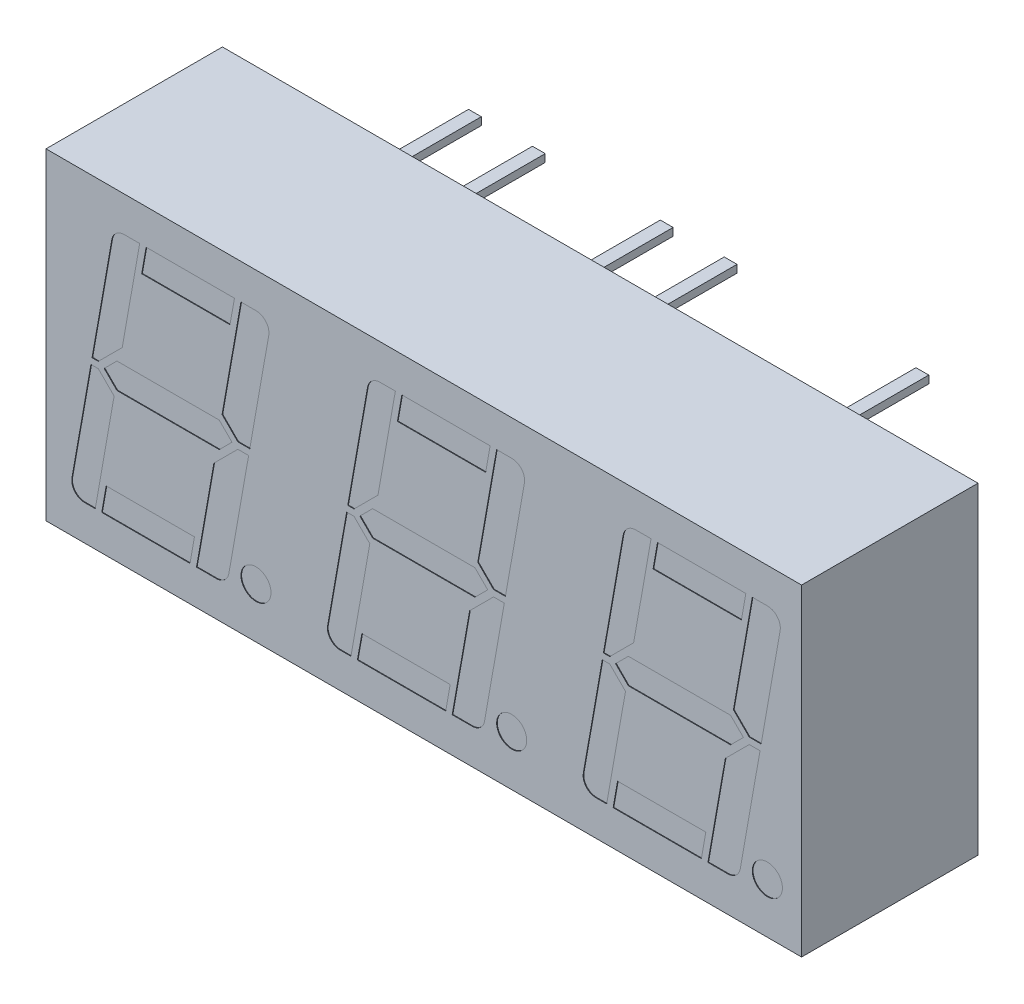
SolidWorks part; units mm, degrees
ref_plane "Front Plane" through (0, 0, 0) normal (0, 0, 1) x (1, 0, 0)
ref_plane "Top Plane" through (0, 0, 0) normal (0, 1, 0) x (1, 0, 0)
ref_plane "Right Plane" through (0, 0, 0) normal (1, 0, 0) x (0, 0, -1)
sketch "Sketch1" plane through (0, 0, 0) normal (0, 0, 1) x (1, 0, 0)
  line L0 (-15.0114, -6.4008) -> (15.0114, 6.4008) construction
  line L1 (-15.0114, 6.4008) -> (15.0114, 6.4008)
  line L2 (-15.0114, 6.4008) -> (-15.0114, -6.4008)
  line L3 (-15.0114, -6.4008) -> (15.0114, -6.4008)
  line L4 (15.0114, 6.4008) -> (15.0114, -6.4008)
  point P4 (0, 0)
  dimension "D1" = 12.8016
  dimension "D2" = 30.0228
extrude "Boss-Extrude1" add sketch "Sketch1" along normal blind 7.0104
sketch "Sketch2" plane through (0, 0, 0) normal (0, 0, -1) x (-1, 0, 0)
  line L0 (-15.0114, 0) -> (15.0114, 0) construction
  line L1 (-15.0114, -6.4008) -> (-15.0114, 6.4008) construction
  line L2 (15.0114, 6.4008) -> (15.0114, -6.4008) construction
  line L3 (0, 6.4008) -> (0, -6.4008) construction
  line L4 (-15.0114, 6.4008) -> (15.0114, 6.4008) construction
  line L5 (15.0114, -6.4008) -> (-15.0114, -6.4008) construction
  line L6 (-1.27, 5.2324) -> (-1.27, 4.9276) construction
  line L7 (-1.524, 5.2324) -> (-1.016, 5.2324)
  line L8 (-1.524, 5.2324) -> (-1.524, 4.9276)
  line L9 (-1.524, 4.9276) -> (-1.016, 4.9276)
  line L10 (-1.016, 5.2324) -> (-1.016, 4.9276)
  line L12 (-1.524, 5.08) -> (-1.016, 5.08) construction
  dimension "D1" = 0.508
  dimension "D2" = 0.3048
  dimension "D3" = 1.27
  dimension "D4" = 5.08
extrude "Boss-Extrude2" add sketch "Sketch2" along normal blind 3.9116
pattern_linear "LPattern1" count 4 spacing 2.54 along (1, 0, 0) count 2 spacing 10.16 along (0, -1, 0) skipping (1, 0), (2, 0) of "Boss-Extrude2"
pattern_linear "LPattern2" count 5 spacing 2.54 along (-1, 0, 0) count 2 spacing 10.16 along (0, -1, 0) skipping (0, 1), (2, 0), (4, 1) of "Boss-Extrude2"
sketch "Sketch3" plane through (0, 0, 7.0104) normal (0, 0, 1) x (1, 0, 0)
  line L0 (15.0114, 6.4008) -> (-15.0114, 6.4008) construction
  line L1 (-15.0114, -6.4008) -> (15.0114, -6.4008) construction
  line L3 (-15.0114, 0) -> (15.0114, 0) construction
  line L6 (0.8823, 5.0038) -> (-0.8823, -5.0038) construction
  line L7 (-2.54, 0) -> (-2.032, 0.508)
  line L8 (-2.032, 0.508) -> (2.032, 0.508)
  line L9 (-2.7722, 0.127) -> (-1.8218, 1.0774)
  line L10 (-1.8218, 1.0774) -> (-1.1295, 5.0038)
  line L11 (-1.1295, 5.0038) -> (-1.7349, 5.0038)
  line L12 (-2.2352, 4.584) -> (-3.021, 0.127)
  line L13 (-3.021, 0.127) -> (-2.7722, 0.127)
  line L14 (0.8823, 5.0038) -> (-0.8715, 5.0038)
  line L15 (-0.8715, 5.0038) -> (-1.048, 4.0032)
  line L16 (-1.048, 4.0032) -> (0.7059, 4.0032)
  line L17 (0, -6.4008) -> (0, 6.4008) construction
  line L18 (-2.032, -0.508) -> (2.032, -0.508)
  line L19 (-2.54, 0) -> (-2.032, -0.508)
  line L20 (2.54, 0) -> (2.032, 0.508)
  line L21 (-2.286, 0.254) -> (-2.4656, 0.4336) construction
  line L22 (-0.9598, 4.5035) -> (-1.2099, 4.5476) construction
  line L23 (-1.9148, 6.4008) -> (-3.0434, 0) construction
  line L24 (2.54, 0) -> (2.032, -0.508)
  line L25 (3.245, 0.127) -> (2.7722, 0.127)
  line L26 (2.7722, 0.127) -> (2.1448, 0.7544)
  line L27 (2.1448, 0.7544) -> (2.8941, 5.0038)
  line L28 (2.8941, 5.0038) -> (3.4995, 5.0038)
  line L29 (3.9998, 4.4076) -> (3.245, 0.127)
  line L30 (1.914, -5.0038) -> (1.1295, -5.0038)
  line L31 (-2.286, -0.254) -> (-2.4656, -0.4336) construction
  line L32 (1.1295, -5.0038) -> (1.8218, -1.0774)
  line L33 (-3.0658, -0.127) -> (-2.7722, -0.127)
  line L34 (3.2002, -0.127) -> (2.4143, -4.584)
  line L35 (-2.8941, -5.0038) -> (-3.3203, -5.0038)
  line L36 (2.286, 0.254) -> (2.4656, 0.4336) construction
  line L37 (-3.8206, -4.4076) -> (-3.0658, -0.127)
  line L38 (-2.7722, -0.127) -> (-2.1448, -0.7544)
  line L39 (-2.1448, -0.7544) -> (-2.8941, -5.0038)
  line L40 (0.7059, 4.0032) -> (2.4597, 4.0032)
  line L41 (2.4597, 4.0032) -> (2.6361, 5.0038)
  line L42 (2.6361, 5.0038) -> (0.8823, 5.0038)
  line L43 (3.2002, -0.127) -> (2.7722, -0.127)
  line L44 (2.7722, -0.127) -> (1.8218, -1.0774)
  line L45 (2.5479, 4.5035) -> (2.7981, 4.4594) construction
  line L46 (2.286, -0.254) -> (2.4656, -0.4336) construction
  line L47 (-2.6281, 2.3555) -> (-1.6275, 2.1791) construction
  line L48 (-0.7059, -4.0032) -> (-2.4597, -4.0032)
  line L49 (-2.4597, -4.0032) -> (-2.6361, -5.0038)
  line L50 (-2.6361, -5.0038) -> (-0.8823, -5.0038)
  line L51 (-0.8823, -5.0038) -> (0.8715, -5.0038)
  line L52 (0.8715, -5.0038) -> (1.048, -4.0032)
  line L53 (1.048, -4.0032) -> (-0.7059, -4.0032)
  line L56 (-15.0114, 6.4008) -> (-15.0114, -6.4008) construction
  line L57 (15.0114, -6.4008) -> (15.0114, 6.4008) construction
  arc A0 (-2.2352, 4.584) -> (-1.7349, 5.0038) centre (-1.7349, 4.4958) cw
  arc A1 (-3.8206, -4.4076) -> (-3.3203, -5.0038) centre (-3.3203, -4.4958) ccw
  arc A2 (2.4143, -4.584) -> (1.914, -5.0038) centre (1.914, -4.4958) cw
  arc A3 (3.9998, 4.4076) -> (3.4995, 5.0038) centre (3.4995, 4.4958) ccw
  circle A4 centre (3.4925, -4.4069) radius 0.5969
  point P12 (0, 0)
  point P32 (0, 0.508)
  point P34 (0, -0.508)
  dimension "D9" = 0.508
  dimension "D14" = 0.508
  dimension "D15" = 1.1938
  dimension "D16" = 3.4925
  dimension "D2" = 0.508
  dimension "D3" = 45
  dimension "D4" = 2.9972
  dimension "D5" = 0.254
  dimension "D6" = 0.127
  dimension "D7" = 2.54
  dimension "D8" = 5.0038
  dimension "D10" = 1.016
  dimension "D11" = 10.0076
  dimension "D12" = 10
  dimension "D13" = 0.127
extrude "Cut-Extrude1" cut sketch "Sketch3" against normal blind 0.0254
pattern_linear "LPattern3" count 2 spacing 10.16 along (1, 0, 0) of "Cut-Extrude1"
pattern_linear "LPattern4" count 2 spacing 10.16 along (-1, 0, 0) of "Cut-Extrude1"
